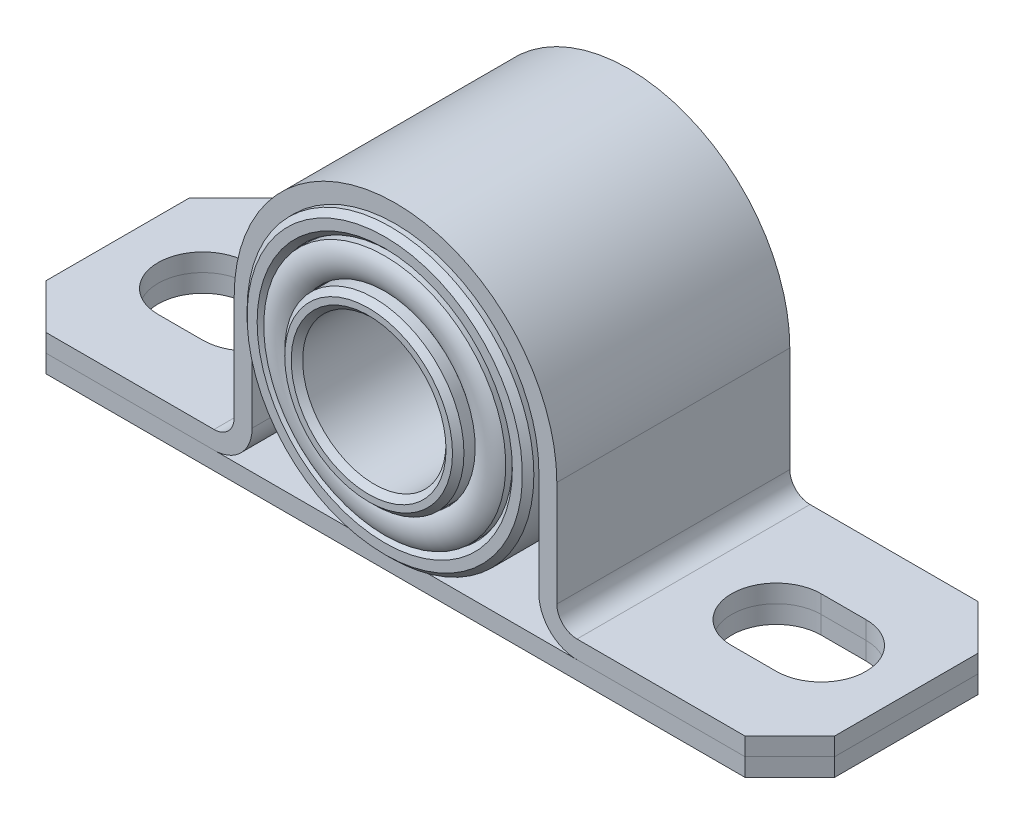
SolidWorks part; units mm, degrees
ref_plane "Front" through (0, 0, 0) normal (0, 0, 1) x (1, 0, 0)
ref_plane "Top" through (0, 0, 0) normal (0, 1, 0) x (1, 0, 0)
ref_plane "Right" through (0, 0, 0) normal (1, 0, 0) x (0, 0, -1)
sketch "Sketch1" plane through (0, 0, 0) normal (0, 1, 0) x (1, 0, 0)
  line L0 (-34.925, -10.3188) -> (34.925, 10.3187) construction
  line L1 (-34.925, -10.3188) -> (34.925, -10.3188)
  line L2 (-34.925, -10.3188) -> (-34.925, 10.3187)
  line L3 (-34.925, 10.3187) -> (34.925, 10.3187)
  line L4 (34.925, -10.3188) -> (34.925, 10.3187)
  line L5 (-27.3844, 0) -> (-23.4156, 0) construction
  line L6 (-23.4156, 0) -> (23.4156, 0) construction
  line L7 (23.4156, 0) -> (27.3844, 0) construction
  line L8 (-27.3844, -3.9688) -> (-23.4156, -3.9688)
  line L9 (23.4156, -3.9688) -> (27.3844, -3.9688)
  line L10 (-27.3844, 3.9688) -> (-23.4156, 3.9688)
  line L11 (23.4156, 3.9688) -> (27.3844, 3.9688)
  arc A0 (-27.3844, -3.9688) -> (-27.3844, 3.9688) centre (-27.3844, 0) cw
  arc A1 (-23.4156, -3.9688) -> (-23.4156, 3.9688) centre (-23.4156, 0) ccw
  arc A2 (23.4156, -3.9688) -> (23.4156, 3.9688) centre (23.4156, 0) cw
  arc A3 (27.3844, -3.9688) -> (27.3844, 3.9688) centre (27.3844, 0) ccw
  point P19 (-25.4, -3.9688)
  point P20 (25.4, -3.9688)
  dimension "Overall Length" = 69.85
  dimension "Mount Width" = 20.6375
  dimension "Hole Width" = 7.9375
  dimension "Hole Length" = 11.9062
  dimension "Hole Centers" = 50.8
extrude "Extrude1" add sketch "Sketch1" along normal blind 1.5875
sketch "Sketch2" plane through (0, 0, 0) normal (0, 0, 1) x (1, 0, 0)
  line L0 (-34.925, 1.5875) -> (-16.0734, 1.5875)
  line L1 (-12.7, 4.9609) -> (-12.7, 14.2875)
  line L2 (12.7, 14.2875) -> (12.7, 4.9609)
  line L3 (16.0734, 1.5875) -> (34.925, 1.5875)
  line L6 (-34.925, 1.5875) -> (-34.925, 3.175)
  line L7 (-34.925, 3.175) -> (-16.0734, 3.175)
  line L8 (-14.2875, 4.9609) -> (-14.2875, 14.2875)
  line L9 (14.2875, 14.2875) -> (14.2875, 4.9609)
  line L10 (16.0734, 3.175) -> (34.925, 3.175)
  line L11 (34.925, 3.175) -> (34.925, 1.5875)
  line L12 (-34.925, 1.5875) -> (-34.925, 0) construction
  line L13 (34.925, 1.5875) -> (34.925, 0) construction
  line L14 (-34.925, 1.5875) -> (34.925, 1.5875) construction
  line L15 (0, 0) -> (0, 28.575) construction
  line L16 (0, 28.575) -> (62.3285, 28.575) construction
  arc A0 (-12.7, 14.2875) -> (12.7, 14.2875) centre (0, 14.2875) cw
  arc A1 (-14.2875, 14.2875) -> (14.2875, 14.2875) centre (0, 14.2875) cw
  arc A2 (14.2875, 4.9609) -> (16.0734, 3.175) centre (16.0734, 4.9609) ccw
  arc A3 (-14.2875, 4.9609) -> (-16.0734, 3.175) centre (-16.0734, 4.9609) cw
  arc A4 (-12.7, 4.9609) -> (-16.0734, 1.5875) centre (-16.0734, 4.9609) cw
  arc A5 (12.7, 4.9609) -> (16.0734, 1.5875) centre (16.0734, 4.9609) ccw
  dimension "D2" = 1.7859
  dimension "Height" = 28.575
  dimension "Center" = 14.2875
extrude "Extrude2" add sketch "Sketch2" along normal up to surface and the other way up to surface separate body up to face at (0, 0.7937, 10.3188) other way up to face at (0, 0.7937, -10.3187)
sketch "Sketch3" plane through (0, 0, 0) normal (0, 1, 0) x (1, 0, 0)
  line L0 (23.4156, -3.9688) -> (27.3844, -3.9688) construction
  line L1 (23.4156, 3.9688) -> (27.3844, 3.9688) construction
  line L2 (-27.3844, -3.9688) -> (-23.4156, -3.9688) construction
  line L3 (-27.3844, 3.9688) -> (-23.4156, 3.9688) construction
  line L4 (23.4156, -3.9688) -> (27.3844, -3.9688)
  line L5 (23.4156, 3.9688) -> (27.3844, 3.9688)
  line L6 (-27.3844, -3.9688) -> (-23.4156, -3.9688)
  line L7 (-27.3844, 3.9688) -> (-23.4156, 3.9688)
  arc A0 (23.4156, 3.9688) -> (23.4156, -3.9688) centre (23.4156, 0) ccw construction
  arc A1 (27.3844, -3.9688) -> (27.3844, 3.9688) centre (27.3844, 0) ccw construction
  arc A2 (-27.3844, 3.9688) -> (-27.3844, -3.9688) centre (-27.3844, 0) ccw construction
  arc A3 (-23.4156, -3.9688) -> (-23.4156, 3.9688) centre (-23.4156, 0) ccw construction
  arc A4 (23.4156, 3.9688) -> (23.4156, -3.9688) centre (23.4156, 0) ccw
  arc A5 (27.3844, -3.9688) -> (27.3844, 3.9688) centre (27.3844, 0) ccw
  arc A6 (-27.3844, 3.9688) -> (-27.3844, -3.9688) centre (-27.3844, 0) ccw
  arc A7 (-23.4156, -3.9688) -> (-23.4156, 3.9688) centre (-23.4156, 0) ccw
extrude "Cut-Extrude1" cut sketch "Sketch3" along normal through all
sketch "Sketch4" plane through (0, 0, 0) normal (1, 0, 0) x (0, 0, -1)
  line L0 (0, 26.9875) -> (-11.2713, 26.9875)
  line L1 (-11.2713, 22.225) -> (-12.7, 22.225)
  line L2 (-11.2713, 26.9875) -> (-11.2713, 25.0825)
  line L3 (-11.2713, 25.0825) -> (-10.5092, 25.0825)
  line L4 (-12.7, 20.6375) -> (0, 20.6375)
  line L5 (0, 20.6375) -> (0, 26.9875)
  line L6 (0, 14.2875) -> (-12.7, 14.2875) construction
  line L7 (10.3187, 26.9875) -> (-10.3188, 26.9875) construction
  line L8 (10.3187, 26.9875) -> (-10.3188, 26.9875) construction
  line L9 (10.3187, 28.575) -> (-10.3188, 28.575) construction
  line L10 (10.3187, 28.575) -> (-10.3188, 28.575) construction
  line L11 (-10.3188, 28.575) -> (-10.3188, 26.9875) construction
  line L12 (-10.5092, 25.0825) -> (-10.5092, 25.0063)
  line L13 (0, 14.2875) -> (0, 20.6375) construction
  line L14 (-10.5092, 25.0063) -> (-11.2712, 25.0063)
  line L15 (-12.7, 22.225) -> (-12.7, 20.6375)
  line L16 (-11.2713, 22.225) -> (-10.5092, 22.225)
  line L17 (-10.5092, 22.225) -> (-10.5092, 22.3012)
  line L18 (-10.5092, 22.3012) -> (-11.2712, 22.3012)
  line L19 (-10.3188, 28.575) -> (-10.3188, 14.2875) construction
  line L20 (-11.7475, 23.6537) -> (-11.2713, 23.6537) construction
  arc A0 (-11.2712, 25.0063) -> (-11.2712, 22.3012) centre (-9.5888, 23.6537) ccw
  dimension "Shaft Dia" = 12.7
  dimension "Flange Dia" = 15.875
  dimension "Bearing Width" = 25.4
  dimension "D1" = 4.7625
  dimension "D2" = 0.0762
  dimension "D3" = 0.762
  dimension "D4" = 2.3812
  dimension "D5" = 0.9525
  dimension "D6" = 2.8575
  dimension "D7" = 0.4762
revolve "Revolve1" add sketch "Sketch4" angle 360 about L6
chamfer "Chamfer3" distance 0.508 angle 45 4 edges at (0, 26.9875, 11.2713) (0, 25.0825, 11.2713) (0, 20.6375, 12.7) (0, 22.225, 12.7)
mirror "Mirror2" about plane through (0, 0, 0) normal (0, 0, 1) of bodies 111
chamfer "Chamfer1" distance 3.9688 angle 45 4 edges at (-34.925, 0.7937, -10.3187) (-34.925, 0.7937, 10.3188) (34.925, 0.7937, -10.3187) (34.925, 0.7937, 10.3188)
chamfer "Chamfer2" distance 3.9688 angle 45 4 edges at (34.925, 2.3812, 10.3188) (34.925, 2.3812, -10.3187) (-34.925, 2.3812, 10.3188) (-34.925, 2.3812, -10.3187)
equation "\"D2@Sketch2\"= \"Center@Sketch2\" / 8"
equation "\"D1@Chamfer2\"=\"D1@Chamfer1\""
equation "\"D1@Chamfer1\"=\"Hole Width@Sketch1\"/2"
equation "\"D5@Sketch4\"=\"D4@Sketch4\"*.4"
equation "\"D6@Sketch4\"=\"D1@Sketch4\"*.6"
equation "\"D7@Sketch4\"=\"D5@Sketch4\"/2"
